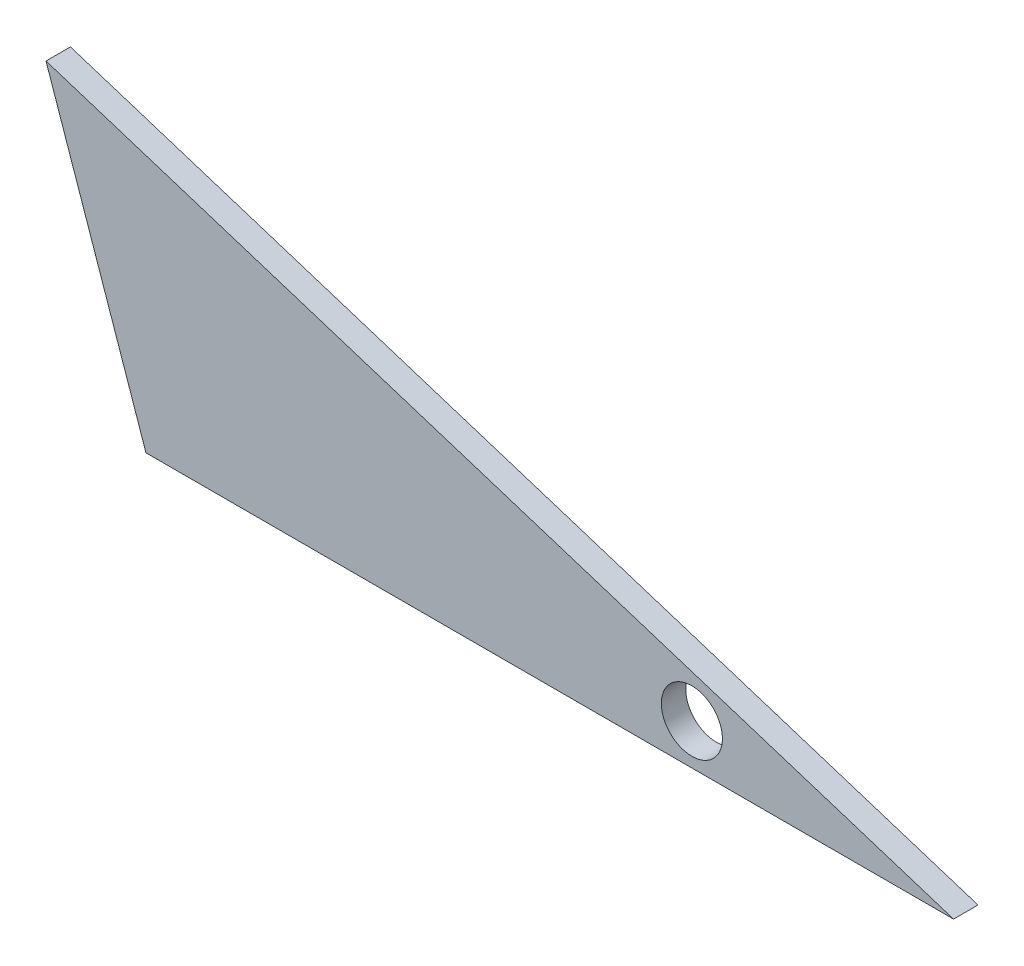
SolidWorks part; units mm, degrees
ref_plane "Front Plane" through (0, 0, 0) normal (0, 0, 1) x (1, 0, 0)
ref_plane "Top Plane" through (0, 0, 0) normal (0, 1, 0) x (1, 0, 0)
ref_plane "Right Plane" through (0, 0, 0) normal (1, 0, 0) x (0, 0, -1)
sketch "Sketch1" plane through (0, 0, 0) normal (0, 0, 1) x (1, 0, 0)
  line L0 (0, 0) -> (-15.5938, 45.1341)
  line L1 (-15.5938, 45.1341) -> (125.9641, 0)
  line L2 (125.9641, 0) -> (0, 0)
  circle A0 centre (85.1442, 6.35) radius 4.7625
  dimension "D4" = 9.525
  dimension "D1" = 6.35
  dimension "D2" = 47.752
  dimension "D3" = 109.06
  dimension "D5" = 6.35
  dimension "D6" = 82.55
extrude "Boss-Extrude1" add sketch "Sketch1" along normal blind 3.81
